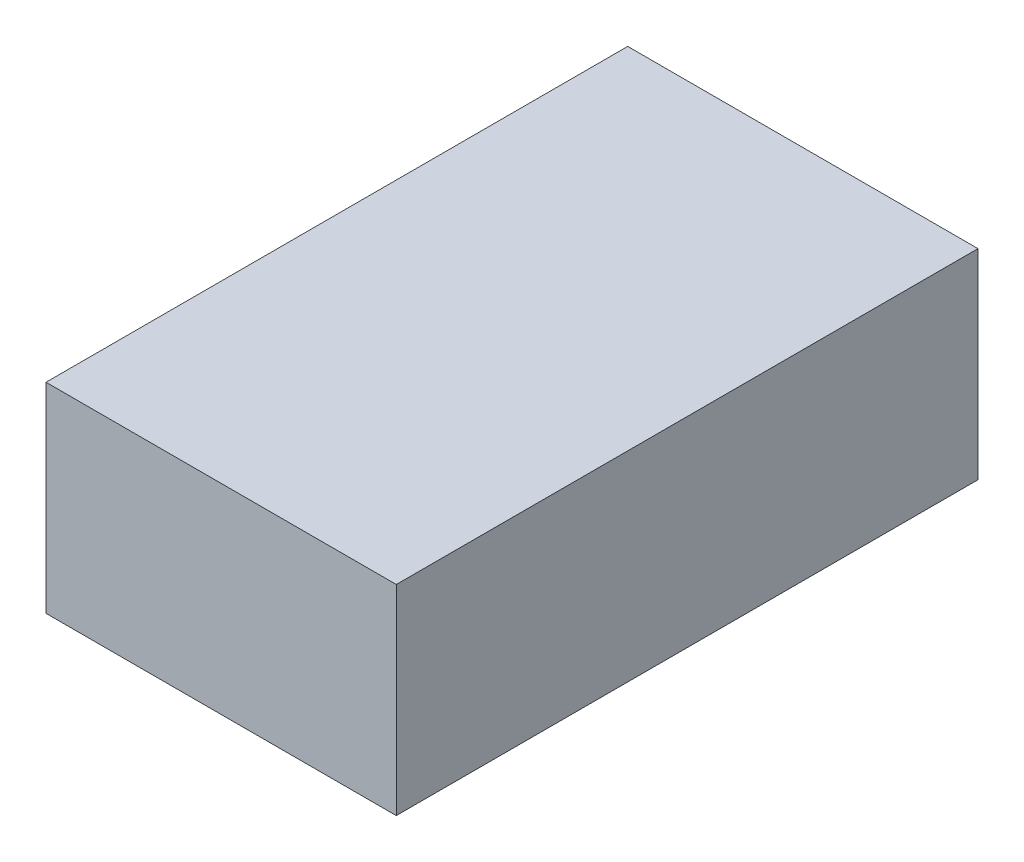
SolidWorks part; units mm, degrees
ref_plane "Front Plane" through (0, 0, 0) normal (0, 0, 1) x (1, 0, 0)
ref_plane "Top Plane" through (0, 0, 0) normal (0, 1, 0) x (1, 0, 0)
ref_plane "Right Plane" through (0, 0, 0) normal (1, 0, 0) x (0, 0, -1)
ref_plane "PL_Box_0_base" through (0, 0, 100) normal (0, 0, 1) x (1, 0, 0)
sketch "SK_Box_0" plane through (0, 0, 100) normal (0, 0, 1) x (1, 0, 0)
  line L0 (-66, 46) -> (-10, 46)
  line L1 (-10, 46) -> (-10, 78)
  line L2 (-10, 78) -> (-66, 78)
  line L3 (-66, 78) -> (-66, 46)
  dimension "P1" = 66
  dimension "P2" = 46
  dimension "P3" = 10
  dimension "P4" = 46
  dimension "P5" = 10
  dimension "P6" = 78
  dimension "P7" = 66
  dimension "P8" = 78
extrude "Box_0" add sketch "SK_Box_0" along normal blind 93
